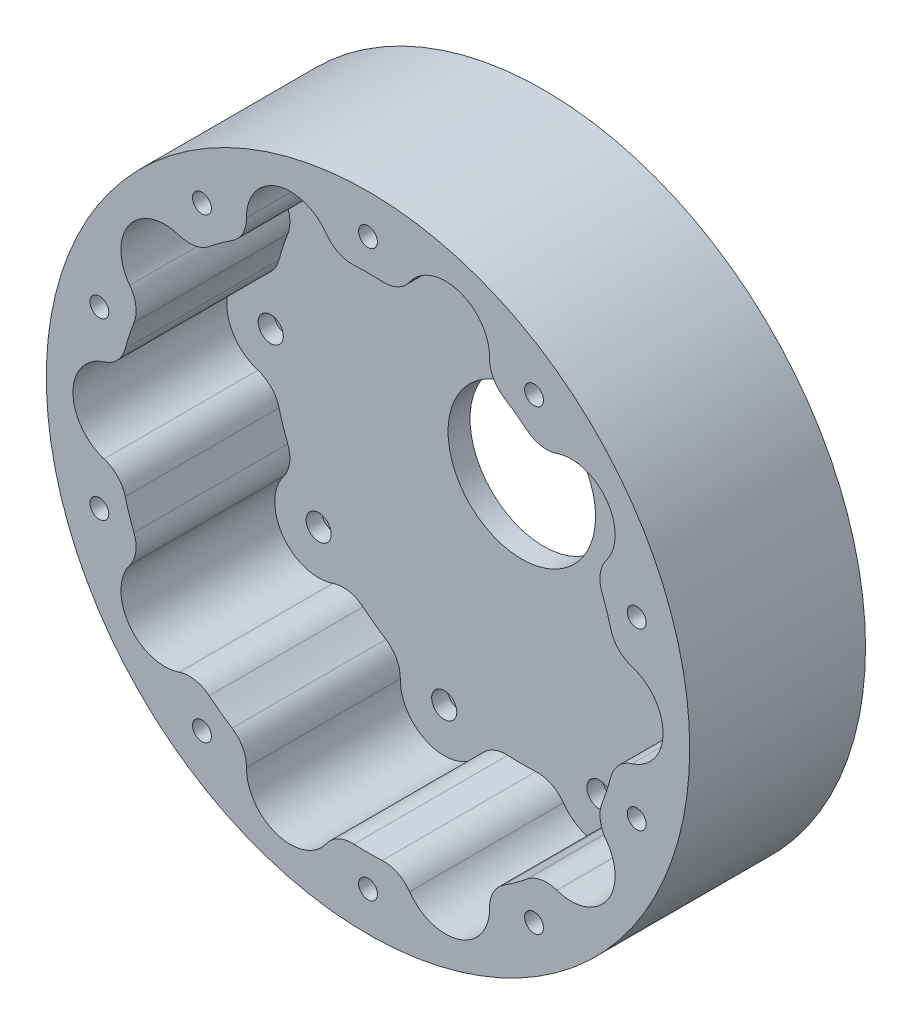
SolidWorks part; units mm, degrees
ref_plane "Front Plane" through (0, 0, 0) normal (0, 0, 1) x (1, 0, 0)
ref_plane "Top Plane" through (0, 0, 0) normal (0, 1, 0) x (1, 0, 0)
ref_plane "Right Plane" through (0, 0, 0) normal (1, 0, 0) x (0, 0, -1)
sketch "Sketch1" plane through (0, 0, 0) normal (0, 0, 1) x (1, 0, 0)
  circle A0 centre (0, 0) radius 102.5
  dimension "D1" = 205
extrude "Boss-Extrude1" add sketch "Sketch1" along normal blind 7
sketch "Sketch3" plane through (0, 0, 7) normal (0, 0, 1) x (1, 0, 0)
  circle A0 centre (0, 0) radius 23.5
  dimension "D1" = 47
extrude "Cut-Extrude1" cut sketch "Sketch3" against normal through all
sketch "Sketch4" plane through (0, 0, 7) normal (0, 0, 1) x (1, 0, 0)
  circle A0 centre (0, 0) radius 80 construction
  circle A1 centre (80, 0) radius 4
  dimension "D1" = 160
  dimension "D2" = 8
extrude "Cut-Extrude2" cut sketch "Sketch4" against normal blind 5
pattern_circular "CirPattern1" count 10 over 360 about axis through (0, 0, 0) along (0, 0, 1) of "Cut-Extrude2"
sketch "Sketch5" plane through (0, 0, 7) normal (0, 0, 1) x (1, 0, 0)
  arc A0 (-13.2561, 84.1186) -> (-38.7193, 75.8451) centre (-24.7214, 76.0845) ccw
  arc A1 (38.7193, 75.8451) -> (13.2561, 84.1186) centre (24.7214, 76.0845) ccw
  arc A2 (75.9052, 38.6013) -> (60.1681, 60.2617) centre (64.7214, 47.0228) ccw
  arc A3 (84.0979, -13.3868) -> (84.0979, 13.3868) centre (80, 0) ccw
  arc A4 (60.1681, -60.2617) -> (75.9052, -38.6013) centre (64.7214, -47.0228) ccw
  arc A5 (13.2561, -84.1186) -> (38.7193, -75.8451) centre (24.7214, -76.0845) ccw
  arc A6 (-38.7193, -75.8451) -> (-13.2561, -84.1186) centre (-24.7214, -76.0845) ccw
  arc A7 (-75.9052, -38.6013) -> (-60.1681, -60.2617) centre (-64.7214, -47.0228) ccw
  arc A8 (-84.0979, 13.3868) -> (-84.0979, -13.3868) centre (-80, 0) ccw
  arc A9 (-60.1681, 60.2617) -> (-75.9052, 38.6013) centre (-64.7214, 47.0228) ccw
  arc A10 (4.5036, 79.8731) -> (-4.5036, 79.8731) centre (0, 0) ccw
  arc A11 (-43.3048, 67.2659) -> (-50.5917, 61.9716) centre (0, 0) ccw
  arc A12 (-74.5722, 28.9653) -> (-77.3556, 20.399) centre (0, 0) ccw
  arc A13 (-77.3556, -20.399) -> (-74.5722, -28.9653) centre (0, 0) ccw
  arc A14 (-50.5917, -61.9716) -> (-43.3048, -67.2659) centre (0, 0) ccw
  arc A15 (50.5917, 61.9716) -> (43.3048, 67.2659) centre (0, 0) ccw
  arc A16 (74.5722, -28.9653) -> (77.3556, -20.399) centre (0, 0) ccw
  arc A17 (43.3048, -67.2659) -> (50.5917, -61.9716) centre (0, 0) ccw
  arc A18 (-4.5036, -79.8731) -> (4.5036, -79.8731) centre (0, 0) ccw
  arc A19 (77.3556, 20.399) -> (74.5722, 28.9653) centre (0, 0) ccw
  circle A20 centre (0, 0) radius 102.5 construction
  circle A21 centre (0, 0) radius 102.5
  arc A22 (13.2561, -84.1186) -> (4.5036, -79.8731) centre (5.0666, -89.8573) ccw
  arc A23 (-13.2561, -84.1186) -> (-4.5036, -79.8731) centre (-5.0666, -89.8573) cw
  arc A24 (-38.7193, -75.8451) -> (-43.3048, -67.2659) centre (-48.7179, -75.6741) ccw
  arc A25 (-60.1681, -60.2617) -> (-50.5917, -61.9716) centre (-56.9157, -69.718) cw
  arc A26 (-75.9052, -38.6013) -> (-74.5722, -28.9653) centre (-83.8937, -32.586) ccw
  arc A27 (-84.0979, -13.3868) -> (-77.3556, -20.399) centre (-87.025, -22.9488) cw
  arc A28 (-84.0979, 13.3868) -> (-77.3556, 20.399) centre (-87.025, 22.9488) ccw
  arc A29 (-75.9052, 38.6013) -> (-74.5722, 28.9653) centre (-83.8937, 32.586) cw
  arc A30 (-60.1681, 60.2617) -> (-50.5917, 61.9716) centre (-56.9157, 69.718) ccw
  arc A31 (-38.7193, 75.8451) -> (-43.3048, 67.2659) centre (-48.7179, 75.6741) cw
  arc A32 (-13.2561, 84.1186) -> (-4.5036, 79.8731) centre (-5.0666, 89.8573) ccw
  arc A33 (13.2561, 84.1186) -> (4.5036, 79.8731) centre (5.0666, 89.8573) cw
  arc A34 (38.7193, 75.8451) -> (43.3048, 67.2659) centre (48.7179, 75.6741) ccw
  arc A35 (60.1681, 60.2617) -> (50.5917, 61.9716) centre (56.9157, 69.718) cw
  arc A36 (75.9052, 38.6013) -> (74.5722, 28.9653) centre (83.8937, 32.586) ccw
  arc A37 (84.0979, 13.3868) -> (77.3556, 20.399) centre (87.025, 22.9488) cw
  arc A38 (84.0979, -13.3868) -> (77.3556, -20.399) centre (87.025, -22.9488) ccw
  arc A39 (75.9052, -38.6013) -> (74.5722, -28.9653) centre (83.8937, -32.586) cw
  arc A40 (60.1681, -60.2617) -> (50.5917, -61.9716) centre (56.9157, -69.718) ccw
  arc A41 (38.7193, -75.8451) -> (43.3048, -67.2659) centre (48.7179, -75.6741) cw
  point P23 (0, 0)
  point P41 (-11.0791, -79.2291)
  point P46 (-55.5329, -57.5856)
  point P51 (-78.775, -13.9463)
  point P56 (-71.9277, 35.02)
  point P59 (-55.5329, 57.5856)
  point P62 (-37.6065, 70.6098)
  point P71 (55.5329, 57.5856)
  point P74 (71.9277, 35.02)
  point P77 (78.775, 13.9463)
  point P80 (78.775, -13.9463)
  point P83 (71.9277, -35.02)
  point P88 (37.6065, -70.6098)
  dimension "D1" = 28
  dimension "D3" = 10
  dimension "D4" = 10
  dimension "D2" = 10
extrude "Boss-Extrude2" add sketch "Sketch5" along normal blind 49
sketch "Sketch6" plane through (0, 0, 56) normal (0, 0, 1) x (1, 0, 0)
  line L0 (0, 0) -> (0, 90) construction
  circle A0 centre (0, 90) radius 3
  circle A1 centre (52.9007, 72.8115) radius 3
  circle A2 centre (85.5951, 27.8115) radius 3
  circle A3 centre (85.5951, -27.8115) radius 3
  circle A4 centre (52.9007, -72.8115) radius 3
  circle A5 centre (0, -90) radius 3
  circle A6 centre (-52.9007, -72.8115) radius 3
  circle A7 centre (-85.5951, -27.8115) radius 3
  circle A8 centre (-85.5951, 27.8115) radius 3
  circle A9 centre (-52.9007, 72.8115) radius 3
  point P25 (0, 0)
  dimension "D1" = 6
  dimension "D2" = 90
  dimension "D3" = 10
extrude "Cut-Extrude5" cut sketch "Sketch6" against normal through all
